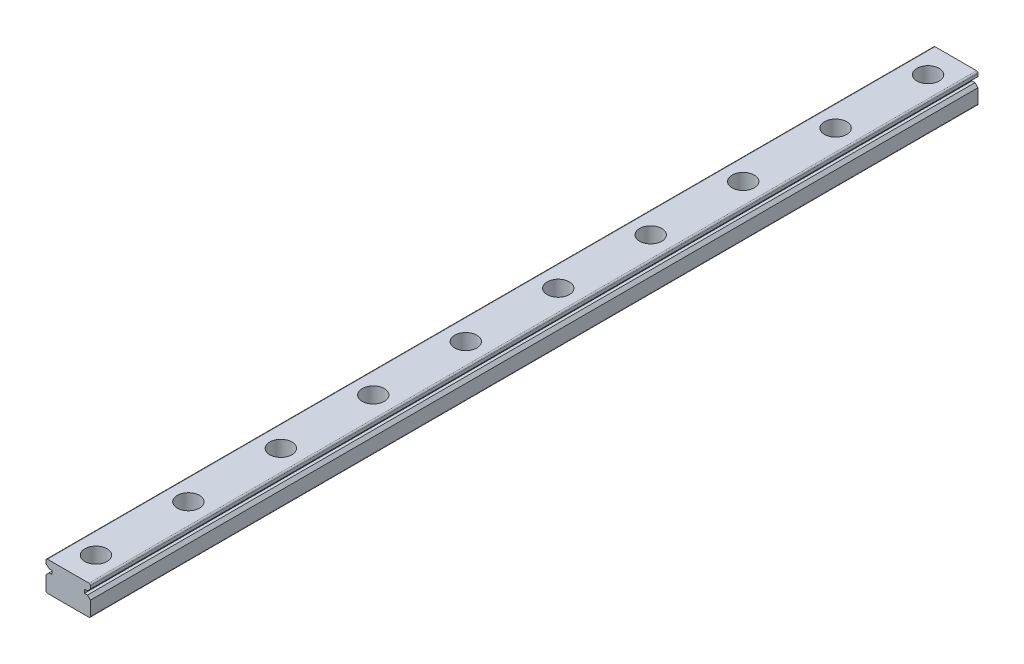
SolidWorks part; units mm, degrees
ref_plane "Front Plane" through (0, 0, 0) normal (0, 0, 1) x (1, 0, 0)
ref_plane "Top Plane" through (0, 0, 0) normal (0, 1, 0) x (1, 0, 0)
ref_plane "Right Plane" through (0, 0, 0) normal (1, 0, 0) x (0, 0, -1)
sketch "Sketch1" plane through (0, 0, 0) normal (0, 0, 1) x (1, 0, 0)
  line L0 (0, -1000) -> (0, 1.5) construction
  line L1 (-5.6, 4) -> (5.6, 4)
  line L2 (-6, 3.6) -> (-6, 2.8)
  line L3 (-5.6, -4) -> (5.6, -4)
  line L4 (6, 3.6) -> (6, 2.8)
  line L5 (-6, 4) -> (6, -4) construction
  line L6 (-6, -4) -> (6, 4) construction
  line L7 (6, 0.2) -> (6, -3.6)
  line L8 (-5.2, 2) -> (-4.4, 2)
  line L9 (-4.4, 2) -> (-4.4, 1)
  line L10 (-5.2, 1) -> (-4.4, 1)
  line L11 (4.4, 2) -> (4.4, 1)
  line L14 (-6, 0.2) -> (-6, -3.6)
  line L15 (4.4, 2) -> (5.2, 2)
  line L16 (4.4, 1) -> (5.2, 1)
  line L17 (0, 1.5) -> (0, 1001.8645) construction
  line L18 (-6, 2.8) -> (-5.2, 2)
  line L19 (-6, 0.2) -> (-5.2, 1)
  line L20 (5.2, 2) -> (6, 2.8)
  line L21 (5.2, 1) -> (6, 0.2)
  arc A0 (-6, -3.6) -> (-5.6, -4) centre (-5.6, -3.6) ccw
  arc A1 (5.6, -4) -> (6, -3.6) centre (5.6, -3.6) ccw
  arc A2 (5.6, 4) -> (6, 3.6) centre (5.6, 3.6) cw
  arc A3 (-5.6, 4) -> (-6, 3.6) centre (-5.6, 3.6) ccw
  point P0 (0, 0)
  point P13 (-6, 2)
  point P14 (6, 2)
  point P15 (6, 1)
  point P16 (-6, 1)
  dimension "D5" = 0.4
  dimension "D1" = 12
  dimension "D2" = 8
  dimension "D3" = 8.8
  dimension "D4" = 5
  dimension "D6" = 2
  dimension "D7" = 5
  dimension "D8" = 4.4
extrude "Boss-Extrude1" add sketch "Sketch1" along normal blind 240
sketch "Sketch2" plane through (0, 4, 0) normal (0, 1, 0) x (1, 0, 0)
  line L0 (5.6, -240) -> (-5.6, -240) construction
  circle A0 centre (0, -232.5) radius 3
  circle A1 centre (0, -207.5) radius 3
  circle A2 centre (0, -182.5) radius 3
  circle A3 centre (0, -157.5) radius 3
  circle A4 centre (0, -132.5) radius 3
  circle A5 centre (0, -107.5) radius 3
  circle A6 centre (0, -82.5) radius 3
  circle A7 centre (0, -57.5) radius 3
  circle A8 centre (0, -32.5) radius 3
  circle A9 centre (0, -7.5) radius 3
  circle A10 centre (0, 17.5) radius 3
  circle A11 centre (0, 42.5) radius 3
  circle A12 centre (0, 67.5) radius 3
  circle A13 centre (0, 92.5) radius 3
  circle A14 centre (0, 117.5) radius 3
  circle A15 centre (0, 142.5) radius 3
  circle A16 centre (0, 167.5) radius 3
  circle A17 centre (0, 192.5) radius 3
  point P39 (0, -240)
  dimension "D1" = 7.5
  dimension "D2" = 6
  dimension "D3" = 18
extrude "Cut-Extrude1" cut sketch "Sketch2" against normal blind 4.5
sketch "Sketch3" plane through (0, 4, 0) normal (0, 1, 0) x (1, 0, 0)
  line L0 (5.6, -240) -> (-5.6, -240) construction
  circle A2 centre (0, -232.5) radius 1.75
  circle A3 centre (0, -207.5) radius 1.75
  circle A4 centre (0, -182.5) radius 1.75
  circle A5 centre (0, -157.5) radius 1.75
  circle A6 centre (0, -132.5) radius 1.75
  circle A7 centre (0, -107.5) radius 1.75
  circle A8 centre (0, -82.5) radius 1.75
  circle A9 centre (0, -57.5) radius 1.75
  circle A10 centre (0, -32.5) radius 1.75
  circle A11 centre (0, -7.5) radius 1.75
  circle A12 centre (0, 17.5) radius 1.75
  circle A13 centre (0, 42.5) radius 1.75
  circle A14 centre (0, 67.5) radius 1.75
  circle A15 centre (0, 92.5) radius 1.75
  circle A16 centre (0, 117.5) radius 1.75
  point P6 (0, -240)
  dimension "D1" = 3.5
  dimension "D2" = 7.5
  dimension "D3" = 15
extrude "Cut-Extrude2" cut sketch "Sketch3" against normal through all
